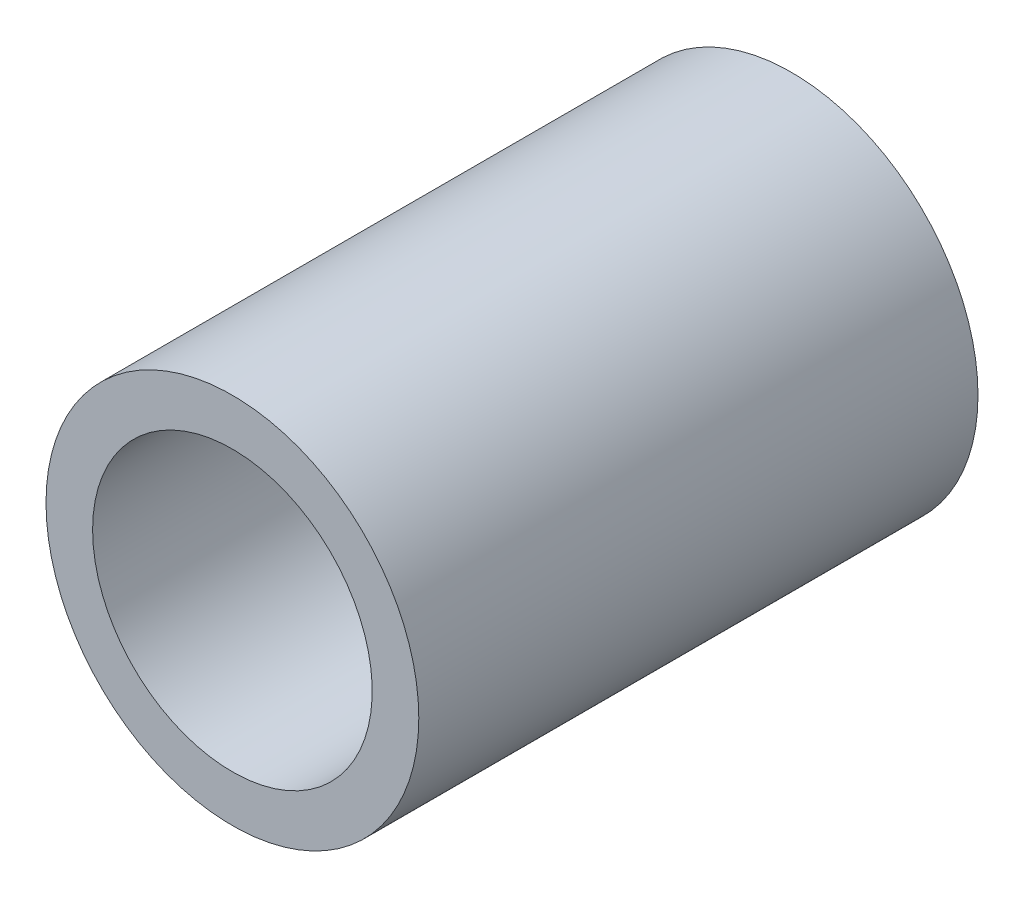
SolidWorks part; units mm, degrees
ref_plane "Front Plane" through (0, 0, 0) normal (0, 0, 1) x (1, 0, 0)
ref_plane "Top Plane" through (0, 0, 0) normal (0, 1, 0) x (1, 0, 0)
ref_plane "Right Plane" through (0, 0, 0) normal (1, 0, 0) x (0, 0, -1)
sketch "Sketch1" plane through (0, 0, 0) normal (0, 0, 1) x (1, 0, 0)
  circle A0 centre (0, 0) radius 9.525
  circle A1 centre (0, 0) radius 12.7
  dimension "D1" = 19.05
  dimension "D2" = 25.4
extrude "Boss-Extrude1" add sketch "Sketch1" along normal blind 38.1
